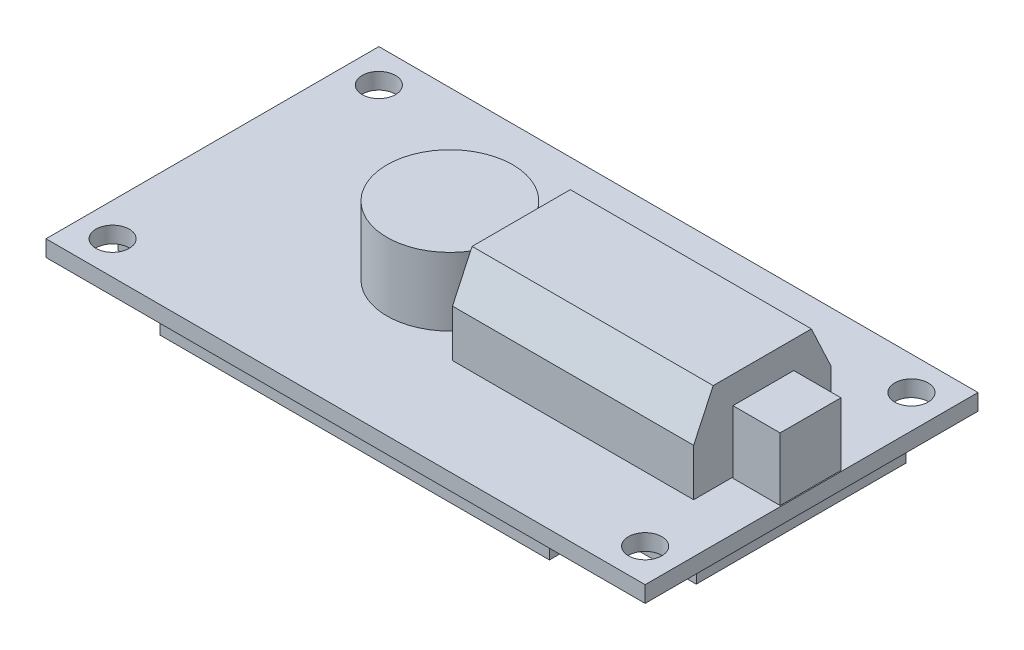
SolidWorks part; units mm, degrees
ref_plane "Front Plane" through (0, 0, 0) normal (0, 0, 1) x (1, 0, 0)
ref_plane "Top Plane" through (0, 0, 0) normal (0, 1, 0) x (1, 0, 0)
ref_plane "Right Plane" through (0, 0, 0) normal (1, 0, 0) x (0, 0, -1)
sketch "Sketch1" plane through (0, 0, 0) normal (0, 1, 0) x (1, 0, 0)
  line L1 (0, 0) -> (57.15, 0)
  line L2 (0, 0) -> (0, -31.75)
  line L3 (0, -31.75) -> (57.15, -31.75)
  line L4 (57.15, 0) -> (57.15, -31.75)
  dimension "D1" = 31.75
  dimension "D2" = 57.15
extrude "PCB" add sketch "Sketch1" along normal blind 1.55
sketch "Sketch2" plane through (0, 1.55, 0) normal (0, 1, 0) x (1, 0, 0)
  line L0 (28.575, 0) -> (28.575, -18.0228) construction
  line L1 (57.15, 0) -> (0, 0) construction
  line L2 (0, -15.875) -> (57.15, -15.875) construction
  line L3 (0, 0) -> (0, -31.75) construction
  line L4 (57.15, -31.75) -> (57.15, 0) construction
  circle A0 centre (3.175, -3.175) radius 1.59
  circle A1 centre (3.175, -28.575) radius 1.59
  circle A2 centre (53.975, -28.575) radius 1.59
  circle A3 centre (53.975, -3.175) radius 1.59
  dimension "D1" = 25.4
  dimension "D2" = 12.7
extrude "Mount Holes" cut sketch "Sketch2" against normal through all
sketch "Sketch4" plane through (0, 1.55, 0) normal (0, 1, 0) x (1, 0, 0)
  line L0 (57.15, -31.75) -> (57.15, 0) construction
  line L1 (0, -15.875) -> (57.15, -15.875) construction
  line L2 (0, 0) -> (0, -31.75) construction
  circle A0 centre (22.65, -15.875) radius 6
  dimension "D1" = 34.5
  dimension "D2" = 12
extrude "Speaker" add sketch "Sketch4" along normal blind 6.5
sketch "Sketch5" plane through (0, 1.55, 0) normal (0, 1, 0) x (1, 0, 0)
  line L0 (0, -15.875) -> (57.15, -15.875) construction
  line L1 (29.45, -9.325) -> (52.45, -9.325)
  line L2 (29.45, -9.325) -> (29.45, -22.425)
  line L3 (29.45, -22.425) -> (52.45, -22.425)
  line L4 (52.45, -9.325) -> (52.45, -22.425)
  line L5 (0, 0) -> (0, -31.75) construction
  line L6 (57.15, -31.75) -> (57.15, 0) construction
  line L7 (29.45, -15.875) -> (52.45, -15.875) construction
  dimension "D1" = 23
  dimension "D2" = 13.1
  dimension "D3" = 4.7
extrude "Terminals" add sketch "Sketch5" along normal blind 8.5
chamfer "Chamfer1" distance 4 angle 25 2 edges at (40.95, 10.05, 9.325) (40.95, 10.05, 22.425)
sketch "Sketch7" plane through (0, 1.55, 0) normal (0, 1, 0) x (1, 0, 0)
  line L1 (52.55, -12.975) -> (57.05, -12.975)
  line L2 (52.55, -12.975) -> (52.55, -18.775)
  line L3 (52.55, -18.775) -> (57.05, -18.775)
  line L4 (57.05, -12.975) -> (57.05, -18.775)
  line L5 (57.05, -15.875) -> (0, -15.875) construction
  line L7 (52.55, -15.875) -> (57.05, -15.875) construction
  line L8 (57.15, -31.75) -> (57.15, 0) construction
  line L9 (0, 0) -> (0, -31.75) construction
  dimension "D1" = 4.5
  dimension "D2" = 5.8
  dimension "D3" = 0.1
extrude "Battery Port" add sketch "Sketch7" along normal blind 6
sketch "Sketch11" plane through (0, 0, 0) normal (0, -1, 0) x (-1, 0, 0)
  line L1 (-24.05, -5.6) -> (-32.05, -5.6)
  line L2 (-24.05, -5.6) -> (-24.05, 0.1)
  line L3 (-24.05, 0.1) -> (-32.05, 0.1)
  line L4 (-32.05, -5.6) -> (-32.05, 0.1)
  line L5 (-57.15, -31.75) -> (-57.15, 0) construction
  line L6 (-57.15, 0) -> (0, 0) construction
  dimension "D1" = 8
  dimension "D2" = 25.1
  dimension "D3" = 5.7
  dimension "D4" = 0.1
extrude "USB Port" add sketch "Sketch11" along normal blind 3 separate body
sketch "Sketch14" plane through (0, 0, 0) normal (0, -1, 0) x (1, 0, 0)
  line L0 (0, 15.875) -> (57.15, 15.875) construction
  line L1 (0, 0) -> (0, 31.75) construction
  line L2 (57.15, 31.75) -> (57.15, 0) construction
  line L3 (28.575, 31.75) -> (28.575, -0.1) construction
  line L4 (10, 30.875) -> (47.15, 30.875)
  line L5 (10, 30.875) -> (10, 0.875)
  line L6 (10, 0.875) -> (47.15, 0.875)
  line L7 (47.15, 30.875) -> (47.15, 0.875)
  line L8 (10, 30.875) -> (47.15, 0.875) construction
  line L9 (10, 0.875) -> (47.15, 30.875) construction
  line L10 (47.15, 25.875) -> (56.15, 25.875)
  line L11 (47.15, 25.875) -> (47.15, 5.875) construction
  line L12 (47.15, 5.875) -> (56.15, 5.875)
  line L13 (56.15, 25.875) -> (56.15, 5.875)
  line L14 (47.15, 25.875) -> (56.15, 5.875) construction
  line L15 (47.15, 5.875) -> (56.15, 25.875) construction
  line L16 (0, 31.75) -> (57.15, 31.75) construction
  line L17 (24.05, -0.1) -> (32.05, -0.1) construction
  line L18 (10, 5.875) -> (1, 5.875)
  line L19 (10, 25.875) -> (1, 25.875)
  line L20 (1, 25.875) -> (1, 5.875)
  point P6 (28.575, 15.875)
  point P11 (51.65, 15.875)
  dimension "D1" = 30
  dimension "D2" = 10
  dimension "D3" = 1
  dimension "D4" = 20
extrude "Surface Components" add sketch "Sketch14" along normal blind 1.85 contours L19 L20 L18 L5 | L7 L4 L5 L6 | L13 L10 L7 L12
sketch "Midline" plane through (0, 1.55, 0) normal (0, 1, 0) x (1, 0, 0)
  line L0 (0, -15.875) -> (57.15, -15.875) construction
